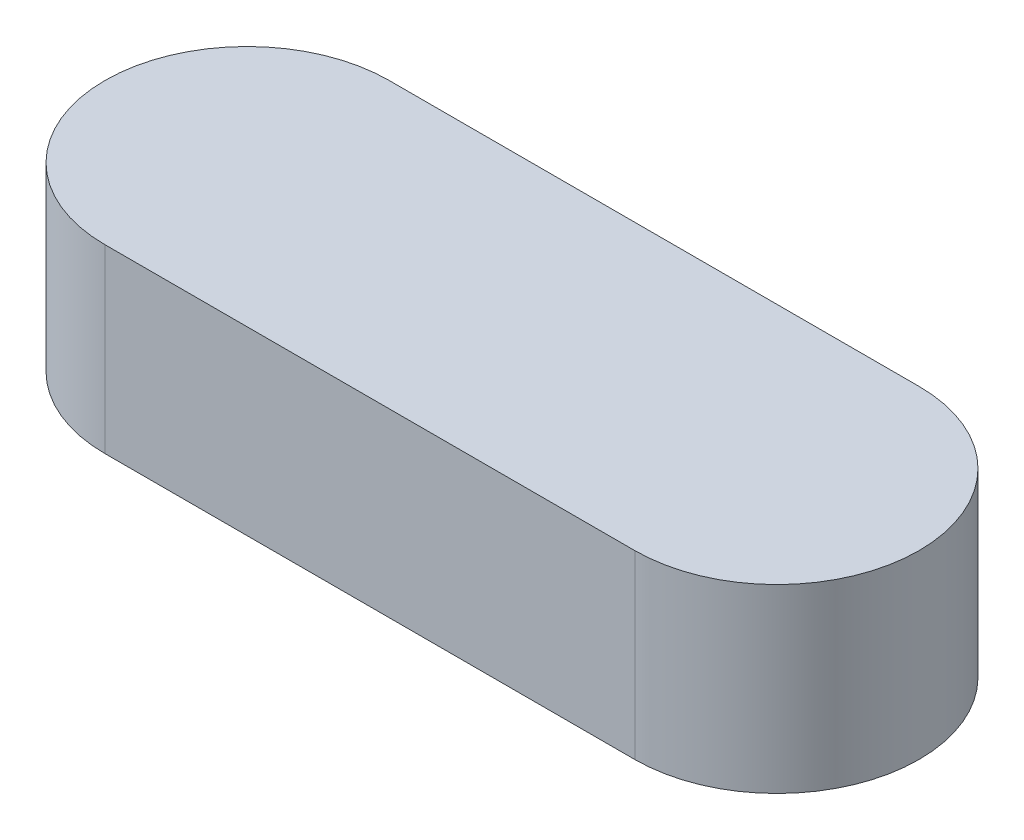
SolidWorks part; units mm, degrees
ref_plane "Front" through (0, 0, 0) normal (0, 0, 1) x (1, 0, 0)
ref_plane "Top" through (0, 0, 0) normal (0, 1, 0) x (1, 0, 0)
ref_plane "Right" through (0, 0, 0) normal (1, 0, 0) x (0, 0, -1)
sketch "Esquisse1" plane through (0, 0, 0) normal (0, 1, 0) x (1, 0, 0)
  line L0 (20.5, 0) -> (-20.5, 0) construction
  line L1 (20.5, -11) -> (-20.5, -11)
  line L2 (20.5, 11) -> (-20.5, 11)
  arc A0 (20.5, -11) -> (20.5, 11) centre (20.5, 0) ccw
  arc A1 (-20.5, 11) -> (-20.5, -11) centre (-20.5, 0) ccw
  point P2 (0, 0)
  dimension "D2" = 11
  dimension "D1" = 41
extrude "Boss.-Extru.1" add sketch "Esquisse1" along normal blind 14
